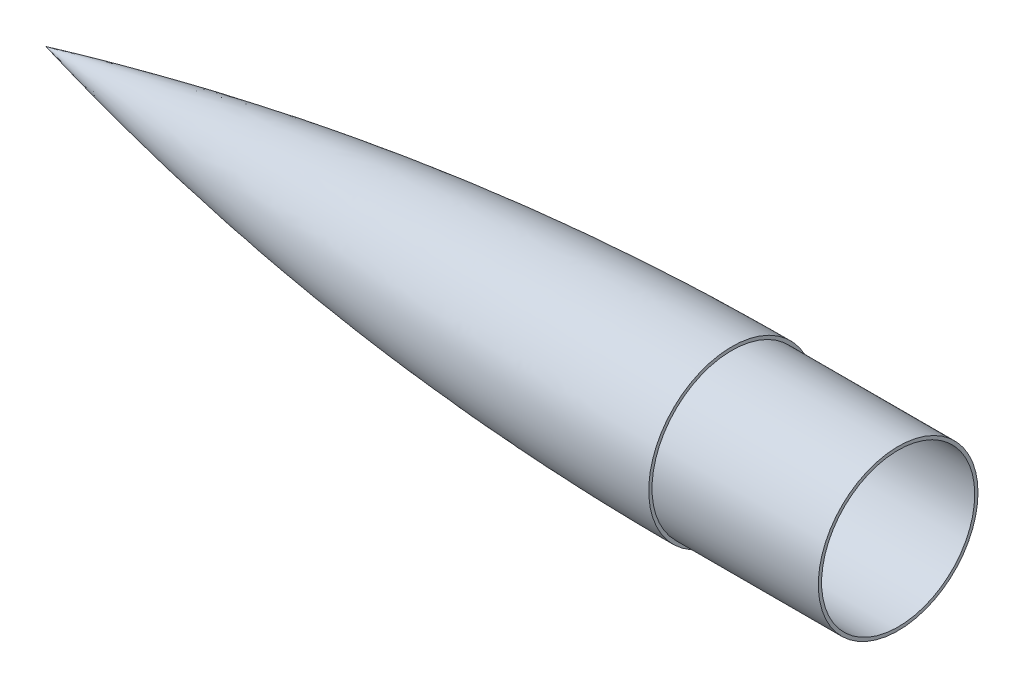
SolidWorks part; units mm, degrees
ref_plane "Front Plane" through (0, 0, 0) normal (0, 0, 1) x (1, 0, 0)
ref_plane "Top Plane" through (0, 0, 0) normal (0, 1, 0) x (1, 0, 0)
ref_plane "Right Plane" through (0, 0, 0) normal (1, 0, 0) x (0, 0, -1)
sketch "Sketch2" plane through (0, 0, 0) normal (0, 0, 1) x (1, 0, 0)
  line L0 (0, 48.7934) -> (0, 50.8)
  line L2 (0, -55) -> (0, 55) construction
  line L3 (-410.6202, 0) -> (-419.1, 0)
  line L4 (55, 0) -> (-55, 0) construction
  line L5 (0, 48.7934) -> (0, 50.8) construction
  arc A1 (0, 50.8) -> (-419.1, 0) centre (0, -1703.3875) ccw
  arc A2 (0, 48.7934) -> (-410.6202, 0) centre (0, -1703.3875) ccw
  dimension "D3" = 2.0066
  dimension "D1" = 50.8
  dimension "D2" = 419.1
revolve "Revolve1" add sketch "Sketch2" angle 360 about L3
sketch "Sketch3" plane through (0, 0, 0) normal (1, 0, 0) x (0, 0, -1)
  circle A0 centre (0, 0) radius 48.7934
  circle A1 centre (0, 0) radius 46.7868
  dimension "D1" = 2.0066
  dimension "D2" = 97.5868
extrude "Boss-Extrude1" add sketch "Sketch3" along normal blind 101.6 separate body
